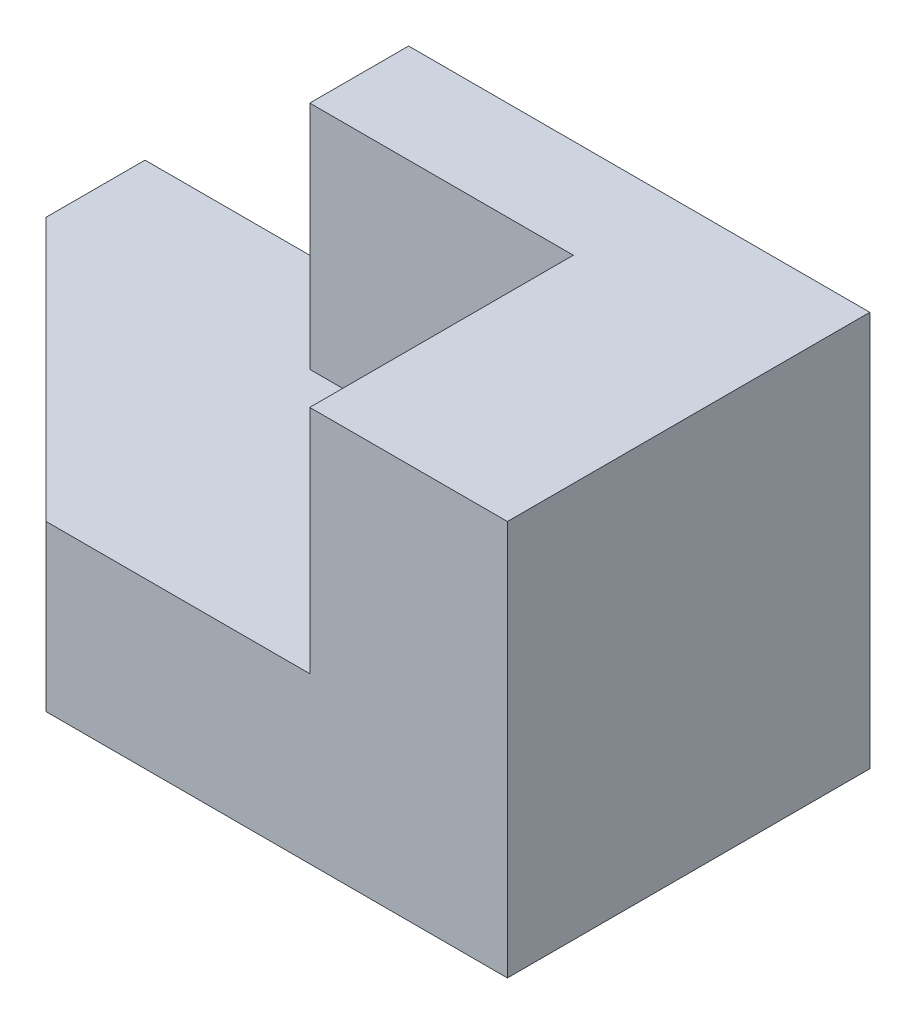
SolidWorks part; units mm, degrees
ref_plane "Front Plane" through (0, 0, 0) normal (0, 0, 1) x (1, 0, 0)
ref_plane "Top Plane" through (0, 0, 0) normal (0, 1, 0) x (1, 0, 0)
ref_plane "Right Plane" through (0, 0, 0) normal (1, 0, 0) x (0, 0, -1)
sketch "Sketch1" plane through (0, 0, 0) normal (0, 0, 1) x (1, 0, 0)
  line L0 (0, 0) -> (70, 0)
  line L1 (70, 0) -> (70, 60)
  line L2 (70, 60) -> (40, 60)
  line L3 (40, 60) -> (40, 25)
  line L4 (40, 25) -> (0, 25)
  line L5 (0, 25) -> (0, 0)
  dimension "D1" = 70
  dimension "D2" = 60
  dimension "D3" = 25
  dimension "D4" = 30
extrude "Boss-Extrude1" add sketch "Sketch1" along normal blind 55 contours L5 L0 L1 L2 L3 L4
sketch "Sketch2" plane through (0, 0, 0) normal (0, 0, -1) x (-1, 0, 0)
  line L0 (-40, 60) -> (0, 60)
  line L1 (0, 60) -> (0, 25)
  line L2 (0, 25) -> (-40, 25)
  line L3 (-40, 25) -> (-40, 60)
extrude "Boss-Extrude2" add sketch "Sketch2" against normal blind 15
sketch "Sketch3" plane through (0, 25, 0) normal (0, 1, 0) x (1, 0, 0)
  line L0 (0, 0) -> (-40, 0)
  line L1 (-40, 0) -> (-40, -15)
  line L2 (-40, -15) -> (0, -55)
  line L3 (0, -55) -> (0, 0)
  dimension "D1" = 40
  dimension "D2" = 40
extrude "Boss-Extrude3" add sketch "Sketch3" against normal blind 25 contours L3 L0 L1 L2
